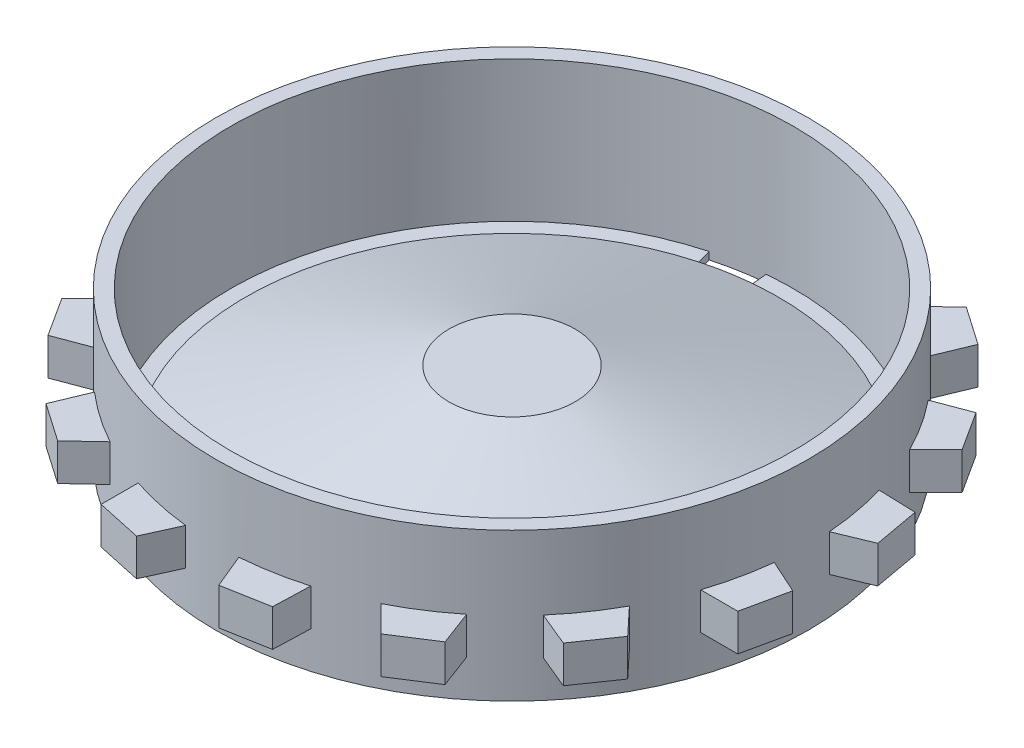
SolidWorks part; units mm, degrees
ref_plane "Front Plane" through (0, 0, 0) normal (0, 0, 1) x (1, 0, 0)
ref_plane "Top Plane" through (0, 0, 0) normal (0, 1, 0) x (1, 0, 0)
ref_plane "Right Plane" through (0, 0, 0) normal (1, 0, 0) x (0, 0, -1)
sketch "Sketch1" plane through (0, 0, 0) normal (0, 1, 0) x (1, 0, 0)
  circle A0 centre (0, 0) radius 40
  dimension "D1" = 80
extrude "Boss-Extrude1" add sketch "Sketch1" along normal blind 10
sketch "Sketch2" plane through (0, 10, 0) normal (0, 1, 0) x (1, 0, 0)
  circle A0 centre (0, 0) radius 38
  dimension "D1" = 76
extrude "Cut-Extrude1" cut sketch "Sketch2" against normal blind 9
sketch "Sketch3" plane through (0, 1, 0) normal (0, 1, 0) x (1, 0, 0)
  line L2 (-10.0181, 36.6557) -> (-9.4908, 34.7264)
  line L3 (-3.5007, 37.8384) -> (-3.3164, 35.8469)
  line L4 (10.0181, -36.6557) -> (9.4908, -34.7264)
  line L5 (3.5007, -37.8384) -> (3.3164, -35.8469)
  arc A0 (-3.5007, 37.8384) -> (-10.0181, 36.6557) centre (0, 0) ccw
  arc A1 (-3.3164, 35.8469) -> (-9.4908, 34.7264) centre (0, 0) ccw
  arc A2 (3.5007, -37.8384) -> (10.0181, -36.6557) centre (0, 0) ccw
  arc A3 (3.3164, -35.8469) -> (9.4908, -34.7264) centre (0, 0) ccw
  dimension "D1" = 2
  dimension "D2" = 2
  dimension "D3" = 36
extrude "Cut-Extrude2" cut sketch "Sketch3" against normal blind 8
sketch "Sketch4" plane through (0, 1, 0) normal (0, 1, 0) x (1, 0, 0)
  circle A0 centre (0, 0) radius 36
extrude "Boss-Extrude2" add sketch "Sketch4" along normal blind 10 draft 70
sketch "Sketch5" plane through (0, 0, 0) normal (0, -1, 0) x (1, 0, 0)
  circle A0 centre (0, 0) radius 35
  dimension "D1" = 70
extrude "Cut-Extrude3" cut sketch "Sketch5" against normal blind 10 draft 70
sketch "Sketch7" plane through (0, 10, 0) normal (0, 1, 0) x (1, 0, 0)
  line L4 (-11.0513, 43.4011) -> (-11.2171, 38.395)
  line L5 (-4.9035, 44.5168) -> (-2.9892, 39.8881)
  line L6 (-11.0513, 43.4011) -> (-4.9035, 44.5168)
  line L8 (6.3988, 44.3266) -> (4.3299, 39.765)
  line L9 (12.5056, 43.0047) -> (12.5028, 37.9958)
  line L10 (6.3988, 44.3266) -> (12.5056, 43.0047)
  line L11 (22.8748, 38.5037) -> (19.2177, 35.0811)
  line L12 (28.0108, 34.9454) -> (26.0915, 30.3189)
  line L13 (22.8748, 38.5037) -> (28.0108, 34.9454)
  line L14 (35.8683, 26.819) -> (31.1797, 25.0564)
  line L15 (39.2517, 21.5661) -> (35.7079, 18.0262)
  line L16 (35.8683, 26.819) -> (39.2517, 21.5661)
  line L17 (43.4011, 11.0513) -> (38.395, 11.2171)
  line L18 (44.5168, 4.9035) -> (39.8881, 2.9892)
  line L19 (43.4011, 11.0513) -> (44.5168, 4.9035)
  line L20 (44.3266, -6.3988) -> (39.765, -4.3299)
  line L21 (43.0047, -12.5056) -> (37.9958, -12.5028)
  line L22 (44.3266, -6.3988) -> (43.0047, -12.5056)
  line L23 (38.5037, -22.8748) -> (35.0811, -19.2177)
  line L24 (34.9454, -28.0108) -> (30.3189, -26.0915)
  line L25 (38.5037, -22.8748) -> (34.9454, -28.0108)
  line L26 (26.819, -35.8683) -> (25.0564, -31.1797)
  line L27 (21.5661, -39.2517) -> (18.0262, -35.7079)
  line L28 (26.819, -35.8683) -> (21.5661, -39.2517)
  line L29 (11.0513, -43.4011) -> (11.2171, -38.395)
  line L30 (4.9035, -44.5168) -> (2.9892, -39.8881)
  line L31 (11.0513, -43.4011) -> (4.9035, -44.5168)
  line L32 (-6.3988, -44.3266) -> (-4.3299, -39.765)
  line L33 (-12.5056, -43.0047) -> (-12.5028, -37.9958)
  line L34 (-6.3988, -44.3266) -> (-12.5056, -43.0047)
  line L35 (-22.8748, -38.5037) -> (-19.2177, -35.0811)
  line L36 (-28.0108, -34.9454) -> (-26.0915, -30.3189)
  line L37 (-22.8748, -38.5037) -> (-28.0108, -34.9454)
  line L38 (-35.8683, -26.819) -> (-31.1797, -25.0564)
  line L39 (-39.2517, -21.5661) -> (-35.7079, -18.0262)
  line L40 (-35.8683, -26.819) -> (-39.2517, -21.5661)
  line L41 (-43.4011, -11.0513) -> (-38.395, -11.2171)
  line L42 (-44.5168, -4.9035) -> (-39.8881, -2.9892)
  line L43 (-43.4011, -11.0513) -> (-44.5168, -4.9035)
  line L44 (-44.3266, 6.3988) -> (-39.765, 4.3299)
  line L45 (-43.0047, 12.5056) -> (-37.9958, 12.5028)
  line L46 (-44.3266, 6.3988) -> (-43.0047, 12.5056)
  line L47 (-38.5037, 22.8748) -> (-35.0811, 19.2177)
  line L48 (-34.9454, 28.0108) -> (-30.3189, 26.0915)
  line L49 (-38.5037, 22.8748) -> (-34.9454, 28.0108)
  line L50 (-26.819, 35.8683) -> (-25.0564, 31.1797)
  line L51 (-21.5661, 39.2517) -> (-18.0262, 35.7079)
  line L52 (-26.819, 35.8683) -> (-21.5661, 39.2517)
  arc A0 (-11.2171, 38.395) -> (-2.9892, 39.8881) centre (0, 0) cw
  circle A1 centre (0, 0) radius 40 construction
  arc A2 (4.3299, 39.765) -> (12.5028, 37.9958) centre (0, 0) cw
  arc A3 (19.2177, 35.0811) -> (26.0915, 30.3189) centre (0, 0) cw
  arc A4 (31.1797, 25.0564) -> (35.7079, 18.0262) centre (0, 0) cw
  arc A5 (38.395, 11.2171) -> (39.8881, 2.9892) centre (0, 0) cw
  arc A6 (39.765, -4.3299) -> (37.9958, -12.5028) centre (0, 0) cw
  arc A7 (35.0811, -19.2177) -> (30.3189, -26.0915) centre (0, 0) cw
  arc A8 (25.0564, -31.1797) -> (18.0262, -35.7079) centre (0, 0) cw
  arc A9 (11.2171, -38.395) -> (2.9892, -39.8881) centre (0, 0) cw
  arc A10 (-4.3299, -39.765) -> (-12.5028, -37.9958) centre (0, 0) cw
  arc A11 (-19.2177, -35.0811) -> (-26.0915, -30.3189) centre (0, 0) cw
  arc A12 (-31.1797, -25.0564) -> (-35.7079, -18.0262) centre (0, 0) cw
  arc A13 (-38.395, -11.2171) -> (-39.8881, -2.9892) centre (0, 0) cw
  arc A14 (-39.765, 4.3299) -> (-37.9958, 12.5028) centre (0, 0) cw
  arc A15 (-35.0811, 19.2177) -> (-30.3189, 26.0915) centre (0, 0) cw
  arc A16 (-25.0564, 31.1797) -> (-18.0262, 35.7079) centre (0, 0) cw
  dimension "D5" = 16
extrude "Boss-Extrude4" add sketch "Sketch7" against normal blind 5
sketch "Sketch8" plane through (0, 10, 0) normal (0, 1, 0) x (1, 0, 0)
  circle A0 centre (0, 0) radius 40
  circle A1 centre (0, 0) radius 38
extrude "Boss-Extrude5" add sketch "Sketch8" along normal blind 10
